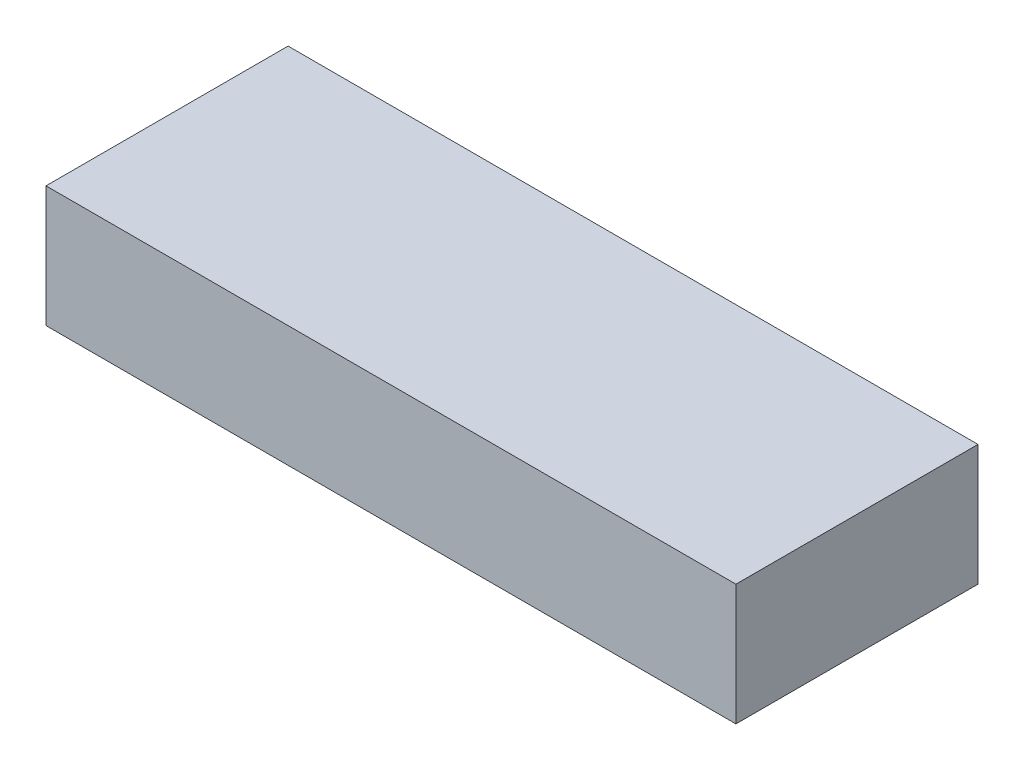
SolidWorks part; units mm, degrees
ref_plane "Front Plane" through (0, 0, 0) normal (0, 0, 1) x (1, 0, 0)
ref_plane "Top Plane" through (0, 0, 0) normal (0, 1, 0) x (1, 0, 0)
ref_plane "Right Plane" through (0, 0, 0) normal (1, 0, 0) x (0, 0, -1)
sketch "Sketch1" plane through (0, 0, 0) normal (0, 1, 0) x (1, 0, 0)
  line L1 (0, 0) -> (57, 0)
  line L2 (0, 0) -> (0, 20)
  line L3 (0, 20) -> (57, 20)
  line L4 (57, 0) -> (57, 20)
extrude "Boss-Extrude1" add sketch "Sketch1" along normal blind 10
